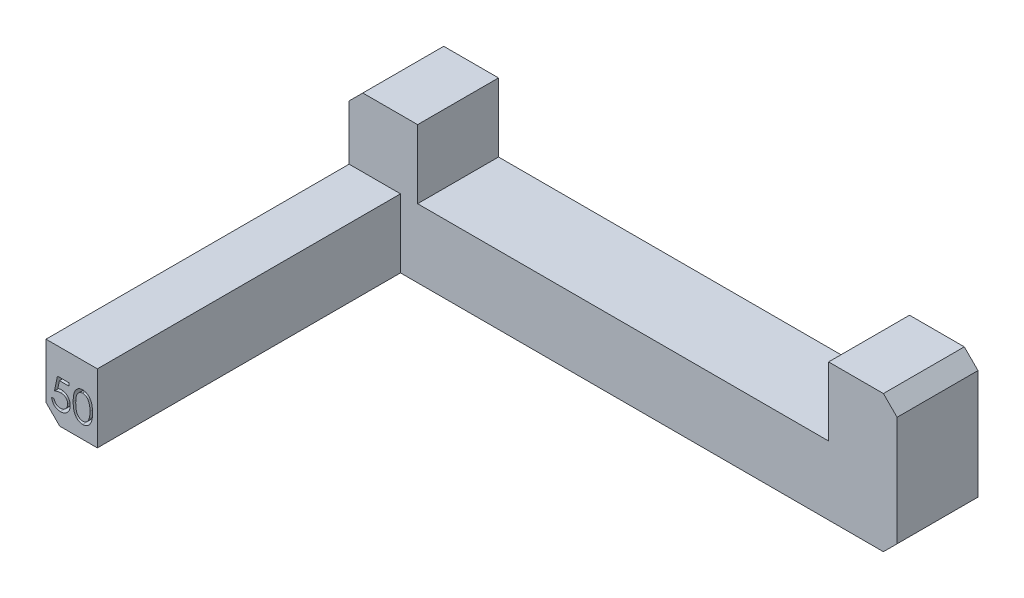
SolidWorks part; units mm, degrees
ref_plane "Front Plane" through (0, 0, 0) normal (0, 0, 1) x (1, 0, 0)
ref_plane "Top Plane" through (0, 0, 0) normal (0, 1, 0) x (1, 0, 0)
ref_plane "Right Plane" through (0, 0, 0) normal (1, 0, 0) x (0, 0, -1)
sketch "Sketch1" plane through (0, 0, 0) normal (0, 0, 1) x (1, 0, 0)
  line L1 (0, 0) -> (-101.6, 0)
  line L2 (0, 0) -> (0, 25.4)
  line L3 (0, 25.4) -> (-101.6, 25.4)
  line L4 (-101.6, 0) -> (-101.6, 25.4)
  line L5 (-12.7, 25.4) -> (-88.9, 25.4)
  line L6 (-12.7, 25.4) -> (-12.7, 12.7)
  line L7 (-12.7, 12.7) -> (-88.9, 12.7)
  line L8 (-88.9, 25.4) -> (-88.9, 12.7)
  point P9 (-50.8, 25.4)
  point P10 (-50.8, 12.7)
  dimension "D1" = 101.6
  dimension "D2" = 25.4
  dimension "D3" = 12.7
  dimension "D4" = 12.7
extrude "Boss-Extrude1" add sketch "Sketch1" along normal blind 15 contours L8 L3 L4 L1 L2 L6 L7
sketch "Sketch2" plane through (0, 0, 15) normal (0, 0, 1) x (1, 0, 0)
  line L1 (-101.6, 0) -> (-92.075, 0)
  line L2 (-101.6, 0) -> (-101.6, 12.7)
  line L3 (-101.6, 12.7) -> (-92.075, 12.7)
  line L4 (-92.075, 0) -> (-92.075, 12.7)
  point P5 (-99.9428, 0.3321)
  dimension "D1" = 9.525
  dimension "D2" = 12.7
extrude "Boss-Extrude2" add sketch "Sketch2" along normal blind 56.2
sketch "Sketch3" plane through (0, 0, 71.2) normal (0, 0, 1) x (1, 0, 0)
  text T0 "50" font "Century Gothic" height in points 20
  point P1 (-103.4257, 1.6878)
  point P2 (-102.4682, 1.9043)
  point P3 (-101.4099, 2.2531)
  point P4 (0, 0)
  point P5 (0, 0)
  point P6 (0, 0)
extrude "Cut-Extrude1" cut sketch "Sketch3" against normal blind 2
chamfer "Chamfer1" distance 2.54 angle 45 4 edges at (0, 0, 7.5) (-101.6, 0, 35.6) (0, 25.4, 7.5) (-101.6, 25.4, 7.5)
